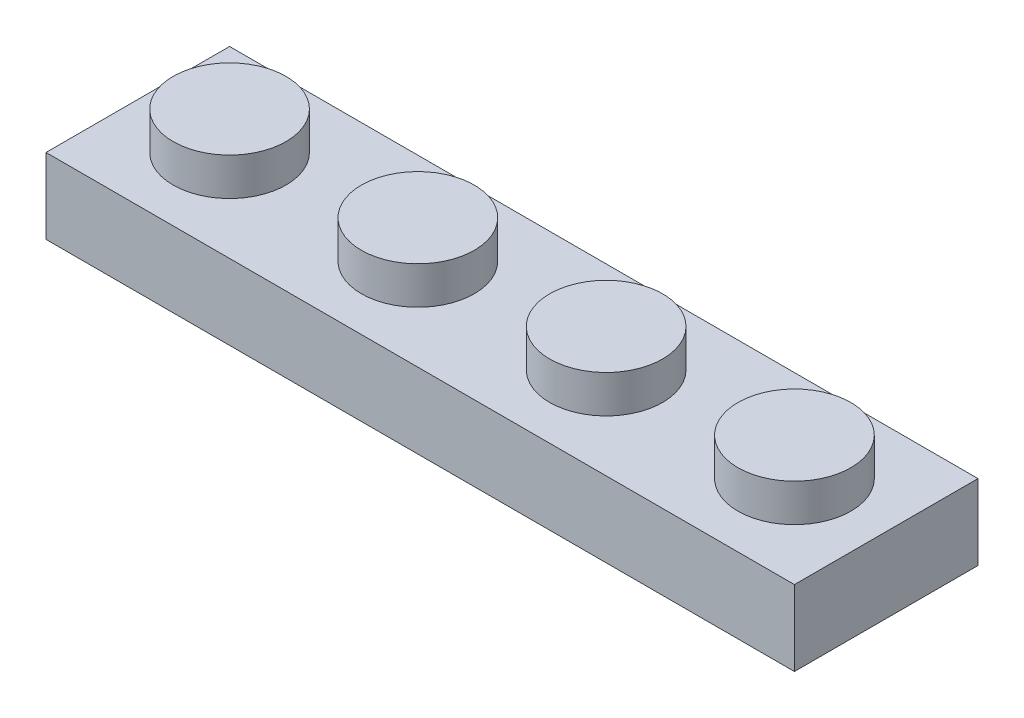
SolidWorks part; units mm, degrees
material "ABS"
ref_plane "Front Plane" through (0, 0, 0) normal (0, 0, 1) x (1, 0, 0)
ref_plane "Top Plane" through (0, 0, 0) normal (0, 1, 0) x (1, 0, 0)
ref_plane "Right Plane" through (0, 0, 0) normal (1, 0, 0) x (0, 0, -1)
sketch "Sketch1" plane through (0, 0, 0) normal (0, 0, 1) x (1, 0, 0)
  line L1 (0, 0) -> (31.8, 0)
  line L2 (0, 0) -> (0, 3.2)
  line L3 (0, 3.2) -> (31.8, 3.2)
  line L4 (31.8, 0) -> (31.8, 3.2)
  dimension "D1" = 3.2
  dimension "D2" = 31.8
extrude "Boss-Extrude1" add sketch "Sketch1" against normal blind 7.8
sketch "Sketch2" plane through (0, 3.2, 0) normal (0, 1, 0) x (1, 0, 0)
  line L0 (0, 7.8) -> (0, 0) construction
  line L1 (31.8, 0) -> (0, 0) construction
  circle A0 centre (3.9, 3.9) radius 2.4
  dimension "D1" = 4.8
  dimension "D2" = 3.9
  dimension "D3" = 3.9
extrude "Boss-Extrude2" add sketch "Sketch2" along normal blind 1.6 contours A0
pattern_linear "LPattern1" count 2 spacing 8 along (0, 0, 1) count 6 spacing 8 along (1, 0, 0) of "Boss-Extrude2"
shell "Shell1" thickness 1.2
sketch "Sketch3" plane through (0, 2, 0) normal (0, -1, 0) x (1, 0, 0)
  line L0 (0, 0) -> (31.8, 0) construction
  line L1 (31.8, -7.8) -> (31.8, 0) construction
  circle A0 centre (23.9, -3.9) radius 1.5
  circle A1 centre (23.9, -3.9) radius 0.6
  dimension "D1" = 3
  dimension "D2" = 1.2
  dimension "D3" = 3.9
  dimension "D4" = 7.9
extrude "Boss-Extrude3" add sketch "Sketch3" along normal offset from surface (1.8 mm away) 0.2 up to face at (15.9, 0, -3.9)
pattern_linear "LPattern2" count 3 spacing 8 along (-1, 0, 0) of "Boss-Extrude3"
